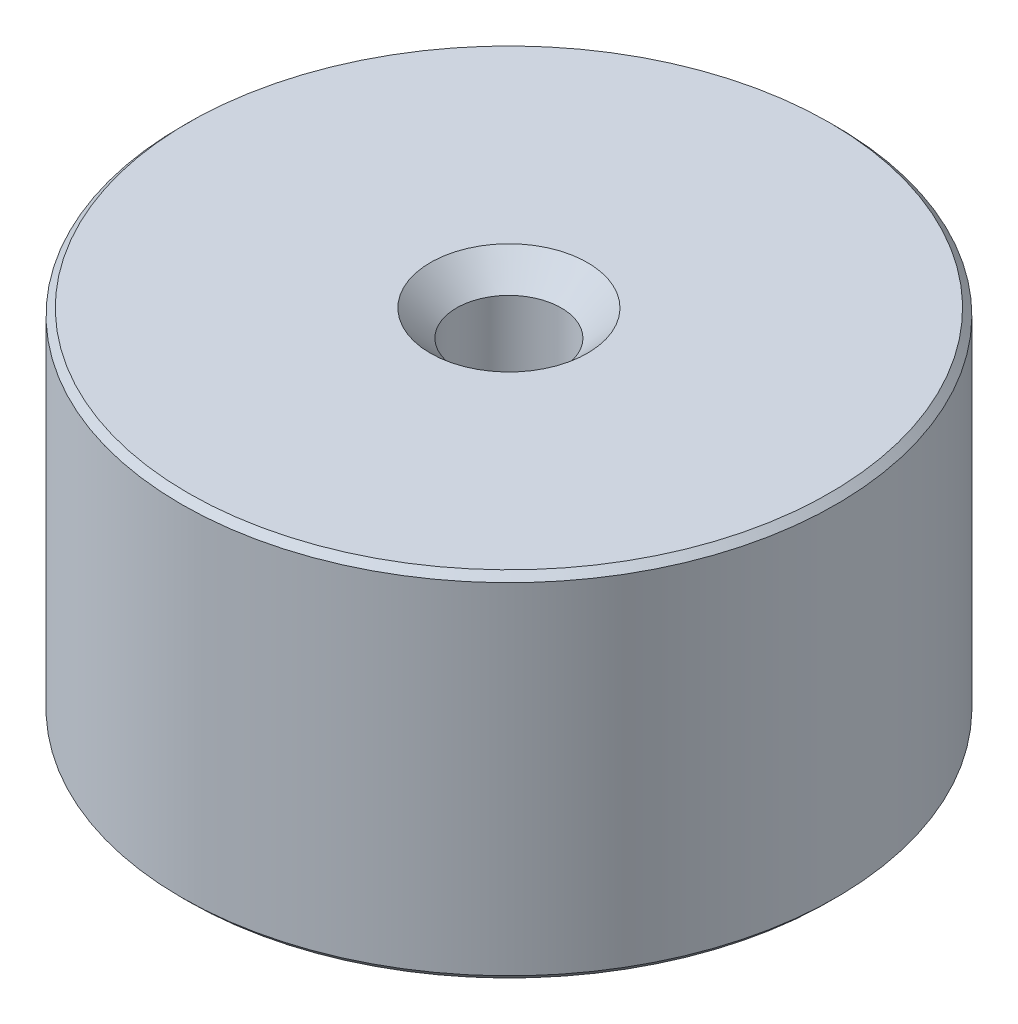
SolidWorks part; units mm, degrees
material "合金钢"
ref_plane "前视基准面" through (0, 0, 0) normal (0, 0, 1) x (1, 0, 0)
ref_plane "上视基准面" through (0, 0, 0) normal (0, 1, 0) x (1, 0, 0)
ref_plane "右视基准面" through (0, 0, 0) normal (1, 0, 0) x (0, 0, -1)
sketch "草图1" plane through (0, 0, 0) normal (0, 1, 0) x (1, 0, 0)
  circle A0 centre (0, 0) radius 25
  dimension "D1" = 50
extrude "凸台-拉伸1" add sketch "草图1" along normal blind 27
sketch "草图9" plane through (0, 27, 0) normal (0, 1, 0) x (1, 0, 0)
  circle A0 centre (0, 0) radius 4
  dimension "D1" = 8
extrude "切除-拉伸1" cut sketch "草图9" against normal blind 12
cosmetic thread "装饰螺纹线1" parameters "D2"=10
sketch "草图10" plane through (0, 0, 0) normal (0, 0, 1) x (1, 0, 0)
  line L0 (-4, 15) -> (0, 12.0938)
  line L1 (-4, 27) -> (-4, 15) construction
  line L2 (0, 12.0938) -> (0, 15)
  line L5 (4, 15) -> (-4, 15) construction
  line L6 (-4, 15) -> (0, 15)
  dimension "D1" = 126
revolve "切除-旋转2" cut sketch "草图10" angle 360 about L2
chamfer "倒角1" distance 2 angle 45 1 edges at (0, 27, 4)
chamfer "倒角2" distance 0.5 angle 45 2 edges at (0, 0, 25) (0, 27, 25)
sketch "草图11" plane through (0, 0, 0) normal (0, -1, 0) x (1, 0, 0)
  circle A0 centre (0, 0) radius 11
  circle A1 centre (0, 0) radius 18
  dimension "D1" = 22
  dimension "D2" = 7
extrude "切除-拉伸2" cut sketch "草图11" against normal blind 2
chamfer "倒角3" distance 0.5 angle 45 2 edges at (0, 0, -11) (0, 2, -11)
